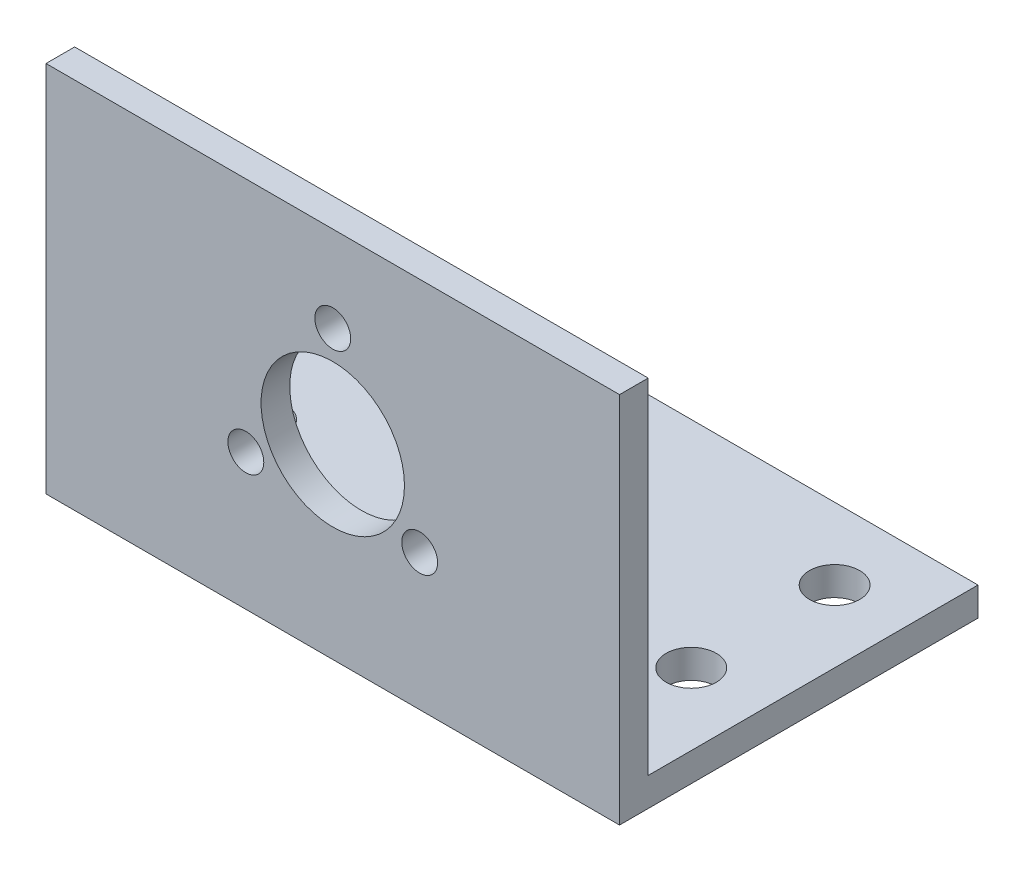
SolidWorks part; units mm, degrees
ref_plane "Front Plane" through (0, 0, 0) normal (0, 0, 1) x (1, 0, 0)
ref_plane "Top Plane" through (0, 0, 0) normal (0, 1, 0) x (1, 0, 0)
ref_plane "Right Plane" through (0, 0, 0) normal (1, 0, 0) x (0, 0, -1)
sketch "Sketch1" plane through (0, 0, 0) normal (0, 1, 0) x (1, 0, 0)
  line L1 (-20, -12.5) -> (20, -12.5)
  line L2 (-20, -12.5) -> (-20, 12.5)
  line L3 (-20, 12.5) -> (20, 12.5)
  line L4 (20, -12.5) -> (20, 12.5)
  line L5 (-20, -12.5) -> (20, 12.5) construction
  line L6 (-20, 12.5) -> (20, -12.5) construction
  point P0 (0, 0)
  dimension "D1" = 40
  dimension "D2" = 25
extrude "Boss-Extrude1" add sketch "Sketch1" along normal blind 2
sketch "Sketch2" plane through (0, 2, 0) normal (0, 1, 0) x (1, 0, 0)
  line L1 (-20, -10.5) -> (20, -10.5)
  line L2 (-20, -10.5) -> (-20, -12.5)
  line L3 (-20, -12.5) -> (20, -12.5)
  line L4 (20, -10.5) -> (20, -12.5)
  point P5 (0, 0)
  dimension "D1" = 2
extrude "Boss-Extrude2" add sketch "Sketch2" along normal blind 24
sketch "Sketch3" plane through (0, 0, 0) normal (0, -1, 0) x (1, 0, 0)
  line L0 (20, -12.5) -> (-20, -12.5) construction
  circle A0 centre (-15, -7.5) radius 1.75
  circle A1 centre (15, -7.5) radius 1.75
  dimension "D5" = 3.5
  dimension "D6" = 3.5
  dimension "D1" = 15
  dimension "D2" = 15
  dimension "D3" = 5
  dimension "D4" = 5
extrude "Cut-Extrude1" cut sketch "Sketch3" against normal through all
pattern_linear "LPattern1" count 2 spacing 10 along (0, 0, 1) of "Cut-Extrude1"
sketch "Sketch5" plane through (0, 0, 12.5) normal (0, 0, 1) x (1, 0, 0)
  line L0 (-20, 26) -> (20, 26) construction
  circle A0 centre (0, 13) radius 5
  dimension "D2" = 10
  dimension "D1" = 13
extrude "Cut-Extrude2" cut sketch "Sketch5" against normal through all
sketch "Sketch6" plane through (0, 0, 12.5) normal (0, 0, 1) x (1, 0, 0)
  circle A0 centre (0, 20) radius 1.25
  circle A1 centre (0, 13) radius 5 construction
  dimension "D2" = 2.5
  dimension "D1" = 7
extrude "Cut-Extrude3" cut sketch "Sketch6" against normal through all
pattern_circular "CirPattern1" count 3 every 120 about axis through (0, 13, 0) along (0, 0, 1) of "Cut-Extrude3"
